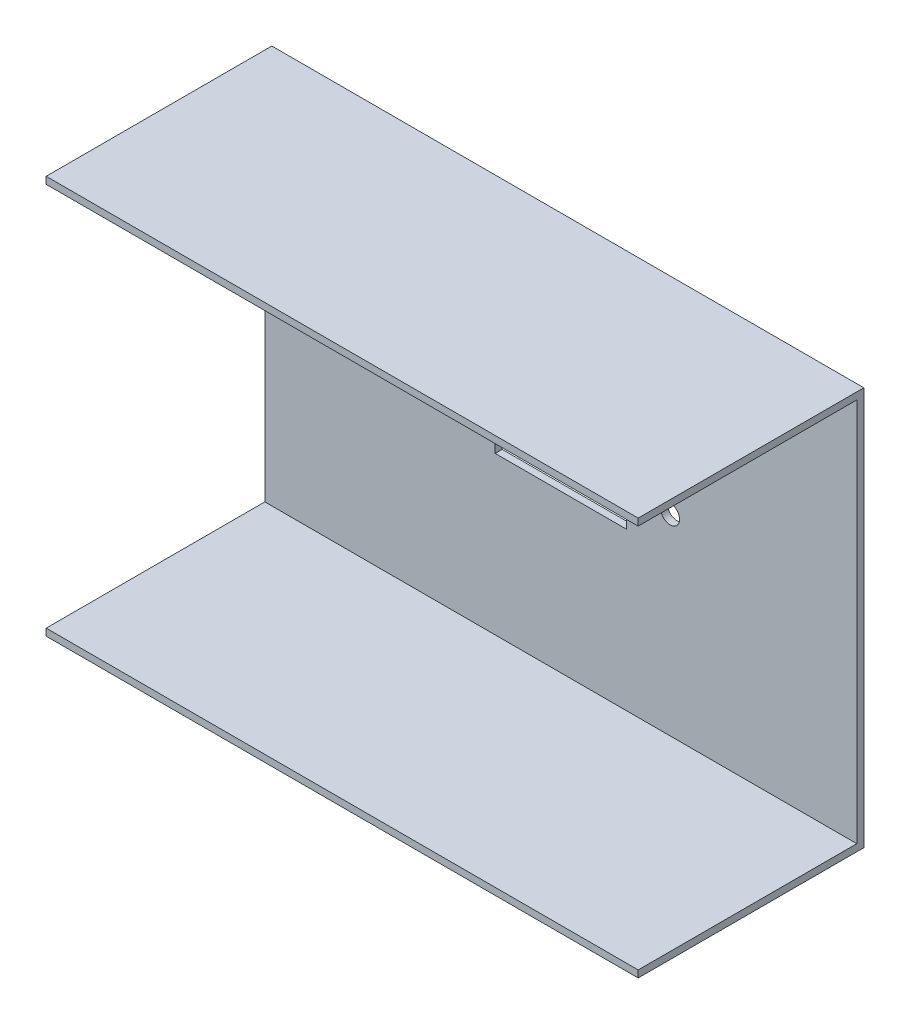
SolidWorks part; units mm, degrees
ref_plane "Front Plane" through (0, 0, 0) normal (0, 0, 1) x (1, 0, 0)
ref_plane "Top Plane" through (0, 0, 0) normal (0, 1, 0) x (1, 0, 0)
ref_plane "Right Plane" through (0, 0, 0) normal (1, 0, 0) x (0, 0, -1)
sketch "Sketch1" plane through (0, 0, 0) normal (1, 0, 0) x (0, 0, -1)
  line L0 (0, 0) -> (0, -1.6002)
  line L1 (0, -1.6002) -> (50, -1.6002)
  line L2 (50, -1.6002) -> (50, -89.4909)
  line L3 (50, -89.4909) -> (0, -89.4909)
  line L4 (0, -89.4909) -> (0, -91.0911)
  line L5 (0, -91.0911) -> (51.6002, -91.0911)
  line L6 (51.6002, -91.0911) -> (51.6002, 0)
  line L7 (51.6002, 0) -> (0, 0)
  line L8 (50, -1.6002) -> (51.6002, -1.6002) construction
  dimension "D1" = 91.0911
  dimension "D2" = 1.6002
  dimension "D3" = 50
extrude "Boss-Extrude1" add sketch "Sketch1" along normal blind 135.3879
sketch "Sketch2" plane through (0, 0, -50) normal (0, 0, 1) x (1, 0, 0)
  line L2 (67.694, -25.5455) -> (67.694, -45.5455) construction
  line L3 (42.694, -45.5455) -> (92.694, -45.5455) construction
  line L5 (52.694, -33.5455) -> (82.694, -33.5455)
  line L8 (52.694, -33.5455) -> (52.694, -53.5455)
  line L28 (52.694, -53.5455) -> (82.694, -53.5455)
  line L29 (82.694, -33.5455) -> (82.694, -53.5455)
  line L30 (37.694, -15.5455) -> (97.694, -15.5455) construction
  line L31 (37.694, -15.5455) -> (37.694, -55.5455) construction
  line L32 (37.694, -55.5455) -> (97.694, -55.5455) construction
  line L33 (97.694, -15.5455) -> (97.694, -55.5455) construction
  line L36 (42.694, -25.5455) -> (92.694, -25.5455) construction
  line L37 (0, -45.5455) -> (135.3879, -45.5455) construction
  line L38 (0, -1.6002) -> (0, -89.4909) construction
  line L39 (135.3879, -1.6002) -> (135.3879, -89.4909) construction
  circle A10 centre (67.694, -25.5455) radius 4.5 construction
  circle A11 centre (67.694, -45.5455) radius 4.5 construction
  circle A12 centre (42.694, -25.5455) radius 2.155
  circle A13 centre (92.694, -25.5455) radius 2.155
  circle A14 centre (42.694, -45.5455) radius 2.155
  circle A15 centre (92.694, -45.5455) radius 2.155
  point P12 (67.694, -35.5455)
  point P13 (67.694, -15.5455)
  point P14 (97.694, -35.5455)
  point P21 (67.694, -25.5455)
  point P24 (67.694, -53.5455)
  point P25 (67.694, -33.5455)
  dimension "D1" = 9
  dimension "D4" = 40
  dimension "D5" = 30
  dimension "D6" = 20
  dimension "D3" = 60
  dimension "D9" = 4.31
  dimension "D2" = 20
  dimension "D7" = 2
  dimension "D8" = 8
  dimension "D10" = 50
  dimension "D11" = 8
  dimension "D12" = 20
  dimension "D13" = 12
extrude "Cut-Extrude1" cut sketch "Sketch2" against normal up to surface (1.6002 mm away) up to face at (67.694, -45.5455, -51.6002)
